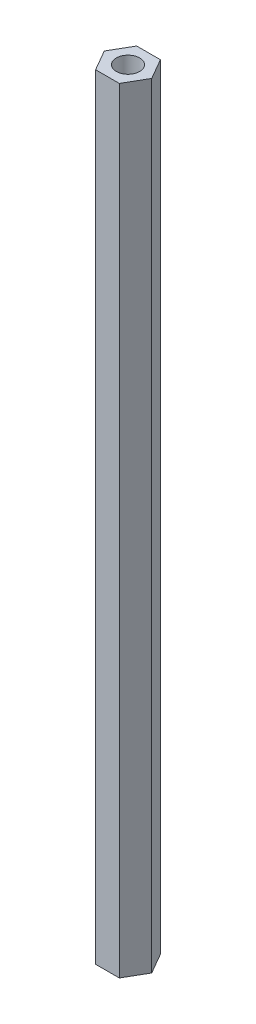
SolidWorks part; units mm, degrees
ref_plane "Front Plane" through (0, 0, 0) normal (0, 0, 1) x (1, 0, 0)
ref_plane "Top Plane" through (0, 0, 0) normal (0, 1, 0) x (1, 0, 0)
ref_plane "Right Plane" through (0, 0, 0) normal (1, 0, 0) x (0, 0, -1)
sketch "Sketch1" plane through (0, 0, 0) normal (0, 1, 0) x (1, 0, 0)
  line L1 (4.0415, 0) -> (2.0207, 3.5)
  line L2 (2.0207, 3.5) -> (-2.0207, 3.5)
  line L3 (-2.0207, 3.5) -> (-4.0415, 0)
  line L4 (-4.0415, 0) -> (-2.0207, -3.5)
  line L5 (-2.0207, -3.5) -> (2.0207, -3.5)
  line L6 (2.0207, -3.5) -> (4.0415, 0)
  circle A0 centre (0, 0) radius 3.5 construction
  circle A1 centre (0, 0) radius 2
  dimension "D1" = 4
  dimension "D2" = 7
extrude "Boss-Extrude1" add sketch "Sketch1" along normal blind 132
